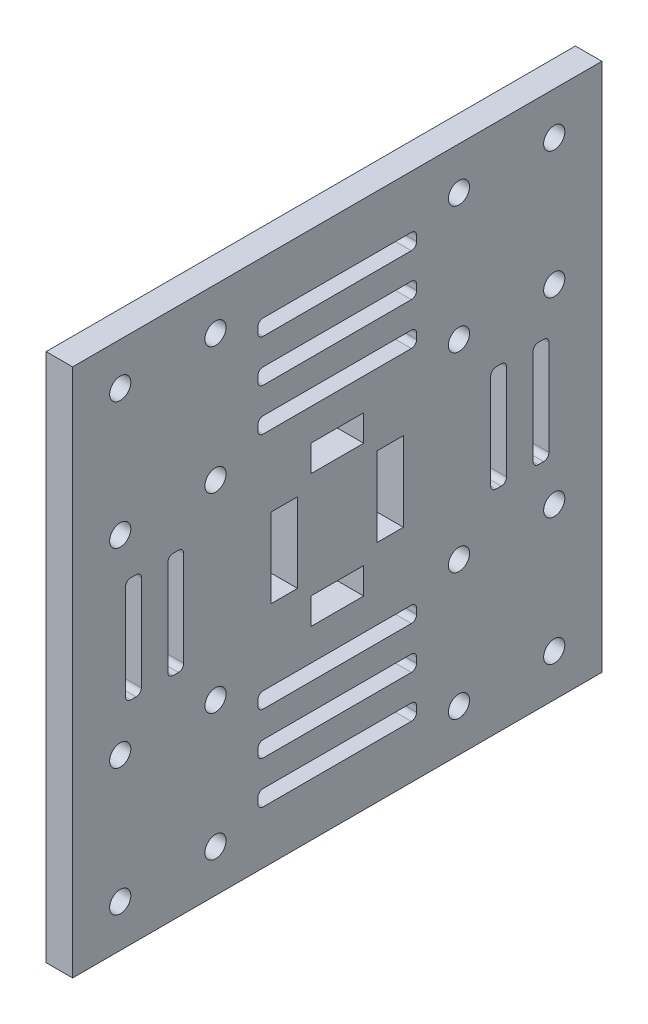
SolidWorks part; units mm, degrees
ref_plane "前视基准面" through (0, 0, 0) normal (0, 0, 1) x (1, 0, 0)
ref_plane "上视基准面" through (0, 0, 0) normal (0, 1, 0) x (1, 0, 0)
ref_plane "右视基准面" through (0, 0, 0) normal (1, 0, 0) x (0, 0, -1)
sketch "草图1" plane through (0, 0, 0) normal (1, 0, 0) x (0, 0, -1)
  line L0 (-119.6937, 80) -> (28.1464, 80) construction
  line L1 (0, 0) -> (-100, 0)
  line L2 (0, 0) -> (0, 100)
  line L3 (0, 100) -> (-100, 100)
  line L4 (-100, 0) -> (-100, 100)
  line L5 (-116.4083, 20) -> (28.1464, 20) construction
  line L6 (-18, 114.1514) -> (-18, -10.1859) construction
  line L7 (-82, 117.4367) -> (-82, -10.1859) construction
  line L8 (-121.6566, 50) -> (60.8952, 50) construction
  line L9 (-62.5, 57.5) -> (-57.5, 57.5)
  line L10 (-62.5, 57.5) -> (-62.5, 42.5)
  line L11 (-62.5, 42.5) -> (-57.5, 42.5)
  line L12 (-57.5, 57.5) -> (-57.5, 42.5)
  line L13 (-42.5, 57.5) -> (-37.5, 57.5)
  line L14 (-42.5, 57.5) -> (-42.5, 42.5)
  line L15 (-42.5, 42.5) -> (-37.5, 42.5)
  line L16 (-37.5, 57.5) -> (-37.5, 42.5)
  line L17 (-55, 40) -> (-45, 40)
  line L18 (-55, 40) -> (-55, 35)
  line L19 (-55, 35) -> (-45, 35)
  line L20 (-45, 40) -> (-45, 35)
  line L21 (-55, 65) -> (-45, 65)
  line L22 (-55, 65) -> (-55, 60)
  line L23 (-55, 60) -> (-45, 60)
  line L24 (-45, 65) -> (-45, 60)
  line L25 (-50, 111.5797) -> (-50, -14.6695) construction
  line L27 (-36, 74) -> (-64, 74)
  line L28 (-35, 73) -> (-35, 72)
  line L29 (-36, 71) -> (-64, 71)
  line L30 (-65, 73) -> (-65, 72)
  line L31 (-36, 82) -> (-64, 82)
  line L32 (-35, 81) -> (-35, 80)
  line L33 (-36, 79) -> (-64, 79)
  line L34 (-65, 81) -> (-65, 80)
  line L35 (-36, 90) -> (-64, 90)
  line L36 (-35, 89) -> (-35, 88)
  line L37 (-36, 87) -> (-64, 87)
  line L38 (-65, 89) -> (-65, 88)
  line L39 (-36, 29) -> (-64, 29)
  line L40 (-35, 28) -> (-35, 27)
  line L41 (-36, 26) -> (-64, 26)
  line L42 (-65, 28) -> (-65, 27)
  line L43 (-36, 21) -> (-64, 21)
  line L44 (-35, 20) -> (-35, 19)
  line L45 (-36, 18) -> (-64, 18)
  line L46 (-65, 20) -> (-65, 19)
  line L47 (-36, 13) -> (-64, 13)
  line L48 (-35, 12) -> (-35, 11)
  line L49 (-36, 10) -> (-64, 10)
  line L50 (-65, 12) -> (-65, 11)
  line L51 (-20, 60) -> (-19, 60)
  line L52 (-21, 59) -> (-21, 41)
  line L53 (-20, 40) -> (-19, 40)
  line L54 (-18, 59) -> (-18, 41)
  line L55 (-12, 60) -> (-11, 60)
  line L56 (-13, 59) -> (-13, 41)
  line L57 (-12, 40) -> (-11, 40)
  line L58 (-10, 59) -> (-10, 41)
  line L59 (-80, 60) -> (-81, 60)
  line L60 (-79, 59) -> (-79, 41)
  line L61 (-80, 40) -> (-81, 40)
  line L62 (-82, 59) -> (-82, 41)
  line L63 (-88, 60) -> (-89, 60)
  line L64 (-87, 59) -> (-87, 41)
  line L65 (-88, 40) -> (-89, 40)
  line L66 (-90, 59) -> (-90, 41)
  circle A0 centre (-91, 92) radius 2
  circle A1 centre (-27, 92) radius 2
  circle A2 centre (-91, 8) radius 2
  circle A3 centre (-27, 8) radius 2
  circle A4 centre (-73, 92) radius 2
  circle A5 centre (-73, 68) radius 2
  circle A6 centre (-91, 68) radius 2
  circle A7 centre (-9, 92) radius 2
  circle A8 centre (-9, 68) radius 2
  circle A9 centre (-27, 68) radius 2
  circle A10 centre (-73, 8) radius 2
  circle A11 centre (-73, 32) radius 2
  circle A12 centre (-91, 32) radius 2
  circle A13 centre (-9, 8) radius 2
  circle A14 centre (-9, 32) radius 2
  circle A15 centre (-27, 32) radius 2
  arc A16 (-64, 29) -> (-65, 28) centre (-64, 28) ccw
  arc A17 (-64, 26) -> (-65, 27) centre (-64, 27) cw
  arc A18 (-64, 21) -> (-65, 20) centre (-64, 20) ccw
  arc A19 (-64, 18) -> (-65, 19) centre (-64, 19) cw
  arc A20 (-64, 13) -> (-65, 12) centre (-64, 12) ccw
  arc A21 (-64, 10) -> (-65, 11) centre (-64, 11) cw
  arc A22 (-35, 11) -> (-36, 10) centre (-36, 11) cw
  arc A23 (-36, 13) -> (-35, 12) centre (-36, 12) cw
  arc A24 (-35, 19) -> (-36, 18) centre (-36, 19) cw
  arc A25 (-36, 21) -> (-35, 20) centre (-36, 20) cw
  arc A26 (-35, 27) -> (-36, 26) centre (-36, 27) cw
  arc A27 (-36, 29) -> (-35, 28) centre (-36, 28) cw
  arc A28 (-11, 40) -> (-10, 41) centre (-11, 41) ccw
  arc A29 (-13, 41) -> (-12, 40) centre (-12, 41) ccw
  arc A30 (-19, 40) -> (-18, 41) centre (-19, 41) ccw
  arc A31 (-21, 41) -> (-20, 40) centre (-20, 41) ccw
  arc A32 (-20, 60) -> (-21, 59) centre (-20, 59) ccw
  arc A33 (-19, 60) -> (-18, 59) centre (-19, 59) cw
  arc A34 (-11, 60) -> (-10, 59) centre (-11, 59) cw
  arc A35 (-12, 60) -> (-13, 59) centre (-12, 59) ccw
  arc A36 (-89, 60) -> (-90, 59) centre (-89, 59) ccw
  arc A37 (-88, 60) -> (-87, 59) centre (-88, 59) cw
  arc A38 (-87, 41) -> (-88, 40) centre (-88, 41) cw
  arc A39 (-89, 40) -> (-90, 41) centre (-89, 41) cw
  arc A40 (-79, 41) -> (-80, 40) centre (-80, 41) cw
  arc A41 (-81, 40) -> (-82, 41) centre (-81, 41) cw
  arc A42 (-81, 60) -> (-82, 59) centre (-81, 59) ccw
  arc A43 (-80, 60) -> (-79, 59) centre (-80, 59) cw
  arc A44 (-64, 71) -> (-65, 72) centre (-64, 72) cw
  arc A45 (-64, 74) -> (-65, 73) centre (-64, 73) ccw
  arc A46 (-35, 72) -> (-36, 71) centre (-36, 72) cw
  arc A47 (-36, 74) -> (-35, 73) centre (-36, 73) cw
  arc A48 (-65, 80) -> (-64, 79) centre (-64, 80) ccw
  arc A49 (-64, 82) -> (-65, 81) centre (-64, 81) ccw
  arc A50 (-36, 82) -> (-35, 81) centre (-36, 81) cw
  arc A51 (-35, 80) -> (-36, 79) centre (-36, 80) cw
  arc A52 (-64, 90) -> (-65, 89) centre (-64, 89) ccw
  arc A53 (-64, 87) -> (-65, 88) centre (-64, 88) cw
  arc A54 (-35, 88) -> (-36, 87) centre (-36, 88) cw
  arc A55 (-36, 90) -> (-35, 89) centre (-36, 89) cw
  point P65 (-55, 37.5)
  point P106 (-11.5, 60)
  point P109 (-65, 29)
  point P112 (-65, 26)
  point P117 (-65, 18)
  point P120 (-65, 13)
  point P123 (-65, 10)
  point P126 (-35, 10)
  point P131 (-35, 18)
  point P134 (-35, 21)
  point P137 (-35, 26)
  point P142 (-10, 40)
  point P149 (-21, 40)
  point P152 (-21, 60)
  point P155 (-18, 60)
  point P158 (-10, 60)
  point P161 (-13, 60)
  point P164 (-90, 60)
  point P169 (-87, 40)
  point P172 (-90, 40)
  point P175 (-79, 40)
  point P180 (-82, 60)
  point P183 (-79, 60)
  point P188 (-65, 74)
  point P191 (-35, 71)
  point P194 (-35, 74)
  point P197 (-65, 79)
  point P200 (-65, 82)
  point P205 (-35, 79)
  point P208 (-65, 90)
  point P211 (-65, 87)
  point P216 (-35, 90)
  dimension "D7" = 4
  dimension "D8" = 4
  dimension "D9" = 4
  dimension "D10" = 4
  dimension "D14" = 9
  dimension "D81" = 1
  dimension "D1" = 100
  dimension "D2" = 100
  dimension "D3" = 20
  dimension "D4" = 20
  dimension "D5" = 18
  dimension "D6" = 18
  dimension "D11" = 12
  dimension "D12" = 9
  dimension "D15" = 12
  dimension "D16" = 9
  dimension "D17" = 12
  dimension "D18" = 12
  dimension "D19" = 9
  dimension "D23" = 50
  dimension "D24" = 50
  dimension "D25" = 5
  dimension "D26" = 5
  dimension "D27" = 5
  dimension "D28" = 5
  dimension "D29" = 10
  dimension "D30" = 10
  dimension "D31" = 15
  dimension "D32" = 15
  dimension "D33" = 15
  dimension "D34" = 15
  dimension "D35" = 12.5
  dimension "D36" = 12.5
  dimension "D37" = 5
  dimension "D38" = 5
  dimension "D39" = 7.5
  dimension "D40" = 7.5
  dimension "D41" = 30
  dimension "D42" = 3
  dimension "D43" = 30
  dimension "D44" = 3
  dimension "D45" = 3
  dimension "D46" = 30
  dimension "D47" = 3
  dimension "D48" = 3
  dimension "D49" = 3
  dimension "D50" = 30
  dimension "D51" = 30
  dimension "D52" = 30
  dimension "D53" = 3
  dimension "D54" = 3
  dimension "D55" = 3
  dimension "D56" = 3
  dimension "D57" = 20
  dimension "D58" = 20
  dimension "D59" = 20
  dimension "D60" = 20
  dimension "D61" = 15
  dimension "D62" = 15
  dimension "D63" = 15
  dimension "D64" = 10
  dimension "D65" = 10
  dimension "D66" = 10
  dimension "D67" = 10
  dimension "D68" = 10
  dimension "D69" = 5
  dimension "D70" = 5
  dimension "D71" = 5
  dimension "D72" = 5
  dimension "D73" = 10
  dimension "D74" = 15
  dimension "D75" = 15
  dimension "D76" = 15
  dimension "D77" = 10
  dimension "D78" = 5
  dimension "D79" = 10
  dimension "D80" = 5
  dimension "D13" = 2
  dimension "D20" = 2
  dimension "D21" = 2
  dimension "D22" = 2
extrude "凸台-拉伸1" add sketch "草图1" along normal blind 5
